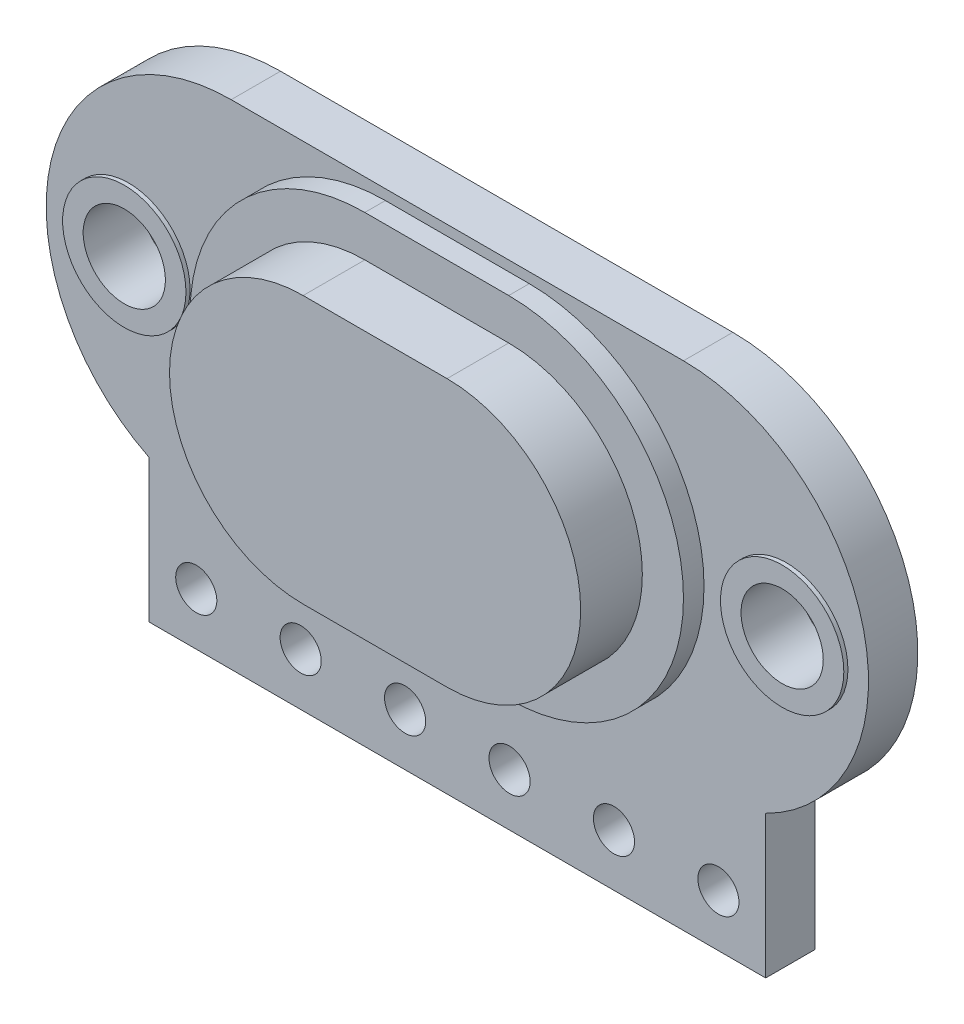
SolidWorks part; units mm, degrees
ref_plane "Plan de face" through (0, 0, 0) normal (0, 0, 1) x (1, 0, 0)
ref_plane "Plan de dessus" through (0, 0, 0) normal (0, 1, 0) x (1, 0, 0)
ref_plane "Plan de droite" through (0, 0, 0) normal (1, 0, 0) x (0, 0, -1)
sketch "Esquisse1" plane through (0, 0, 0) normal (0, 0, 1) x (1, 0, 0)
  line L0 (-7.5, -4.0311) -> (-7.5, -7.5)
  line L1 (0, 19.431) -> (0, -15.0057) construction
  line L2 (-5.5, 0) -> (5.5, 0) construction
  line L5 (-7.5, -7.5) -> (7.5, -7.5)
  line L6 (7.5, -4.0311) -> (7.5, -7.5)
  line L7 (-6.35, -6.23) -> (-3.81, -6.23) construction
  line L8 (-5.5, 4.5) -> (5.5, 4.5)
  circle A2 centre (-8, 0) radius 1
  circle A3 centre (8, 0) radius 1
  circle A4 centre (-6.35, -6.23) radius 0.5
  circle A5 centre (-3.81, -6.23) radius 0.5
  circle A6 centre (-1.27, -6.23) radius 0.5
  circle A7 centre (1.27, -6.23) radius 0.5
  circle A8 centre (3.81, -6.23) radius 0.5
  circle A9 centre (6.35, -6.23) radius 0.5
  arc A10 (-5.5, 4.5) -> (-7.5, -4.0311) centre (-5.5, 0) ccw
  arc A11 (7.5, -4.0311) -> (5.5, 4.5) centre (5.5, 0) ccw
  point P7 (0, 0)
  point P8 (0, 0)
  dimension "D1" = 20
  dimension "D3" = 2
  dimension "D6" = 1
  dimension "D2" = 16
  dimension "D5" = 4.5
  dimension "D4" = 15
  dimension "D8" = 2.54
  dimension "D9" = 1.27
  dimension "D10" = 12
  dimension "D11" = 8.5311
  dimension "D7" = 6
extrude "Boss.-Extru.1" add sketch "Esquisse1" along normal mid plane 1.2
sketch "Esquisse2" plane through (0, 0, 0.6) normal (0, 0, 1) x (1, 0, 0)
  line L0 (-1.75, 0) -> (1.75, 0) construction
  line L1 (-1.75, 4.25) -> (1.75, 4.25)
  line L2 (-1.75, -4.25) -> (1.75, -4.25)
  arc A0 (-1.75, 4.25) -> (-1.75, -4.25) centre (-1.75, 0) ccw
  arc A1 (1.75, -4.25) -> (1.75, 4.25) centre (1.75, 0) ccw
  point P3 (0, 0)
  dimension "D2" = 12
  dimension "D1" = 8.5
extrude "Boss.-Extru.2" add sketch "Esquisse2" along normal blind 0.5
sketch "Esquisse4" plane through (0, 0, 1.1) normal (0, 0, 1) x (1, 0, 0)
  line L4 (-1.75, -3.25) -> (1.75, -3.25)
  line L5 (1.75, 3.25) -> (-1.75, 3.25)
  line L6 (-1.75, -3.25) -> (1.75, -3.25)
  line L7 (1.75, 3.25) -> (-1.75, 3.25)
  arc A4 (-1.75, 3.25) -> (-1.75, -3.25) centre (-1.75, 0) ccw
  arc A5 (1.75, -3.25) -> (1.75, 3.25) centre (1.75, 0) ccw
  arc A6 (-1.75, 3.25) -> (-1.75, -3.25) centre (-1.75, 0) ccw
  arc A7 (1.75, -3.25) -> (1.75, 3.25) centre (1.75, 0) ccw
  dimension "D1" = 1
extrude "Boss.-Extru.4" add sketch "Esquisse4" along normal blind 1.5
sketch "Esquisse3" plane through (0, 0, 0.6) normal (0, 0, 1) x (1, 0, 0)
  line L0 (-6.35, -6.23) -> (-3.81, -6.23) construction
  circle A0 centre (-8, 0) radius 1.5
  circle A1 centre (8, 0) radius 1.5
  circle A2 centre (8, 0) radius 1 construction
  circle A3 centre (-8, 0) radius 1 construction
  circle A4 centre (8, 0) radius 1
  circle A5 centre (-8, 0) radius 1
  circle A6 centre (-6.35, -6.23) radius 0.65
  circle A7 centre (-6.35, -6.23) radius 0.5 construction
  circle A8 centre (-3.81, -6.23) radius 0.65
  circle A9 centre (-1.27, -6.23) radius 0.65
  circle A10 centre (1.27, -6.23) radius 0.65
  circle A11 centre (3.81, -6.23) radius 0.65
  circle A12 centre (6.35, -6.23) radius 0.65
  circle A13 centre (6.35, -6.23) radius 0.5 construction
  circle A14 centre (3.81, -6.23) radius 0.5 construction
  circle A15 centre (1.27, -6.23) radius 0.5 construction
  circle A16 centre (-1.27, -6.23) radius 0.5 construction
  circle A17 centre (-3.81, -6.23) radius 0.5 construction
  circle A18 centre (6.35, -6.23) radius 0.5
  circle A19 centre (3.81, -6.23) radius 0.5
  circle A20 centre (1.27, -6.23) radius 0.5
  circle A21 centre (-1.27, -6.23) radius 0.5
  circle A22 centre (-3.81, -6.23) radius 0.5
  circle A23 centre (-6.35, -6.23) radius 0.5
  dimension "D1" = 3
  dimension "D2" = 1.3
  dimension "D4" = 2.54
  dimension "D3" = 6
extrude "Boss.-Extru.3" add sketch "Esquisse3" along normal blind 0.1
mirror "Symétrie1" about plane through (0, 0, 0) normal (0, 0, 1) of "Boss.-Extru.3"
sketch "Croquis1" plane through (7.5, 0, 0) normal (1, 0, 0) x (0, 0, -1)
  line L0 (0.6, -7.5) -> (0.6, -4.0311) construction
  line L1 (0.6, -5.5655) -> (1.0462, -5.5655)
  line L2 (0.6, -5.5655) -> (0.6, -6.8978)
  line L3 (0.6, -6.8978) -> (1.0462, -6.8978)
  line L4 (1.0462, -5.5655) -> (1.0462, -6.8978)
  line L6 (-0.6, -5.58) -> (-1.2756, -5.58)
  line L7 (-0.6, -5.58) -> (-0.6, -6.9333)
  line L8 (-0.6, -6.9333) -> (-1.2756, -6.9333)
  line L9 (-1.2756, -5.58) -> (-1.2756, -6.9333)
extrude "Cortar-Extruir1" cut sketch "Croquis1" against normal blind 17
